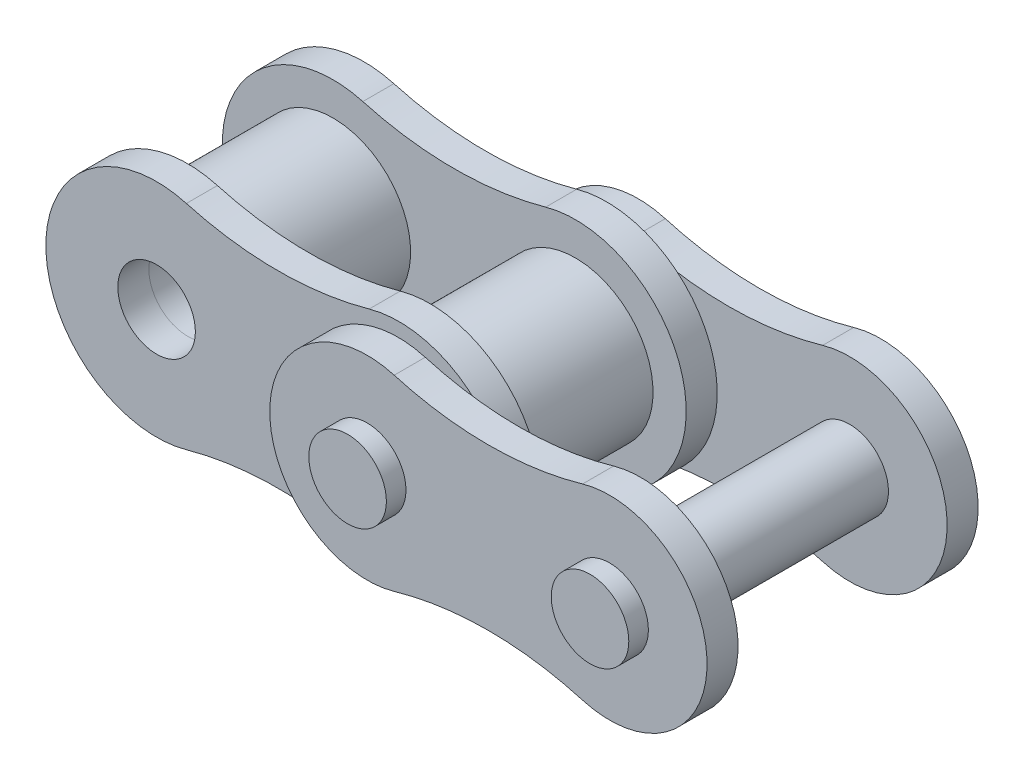
SolidWorks part; units mm, degrees
ref_plane "Front Plane" through (0, 0, 0) normal (0, 0, 1) x (1, 0, 0)
ref_plane "Top Plane" through (0, 0, 0) normal (0, 1, 0) x (1, 0, 0)
ref_plane "Right Plane" through (0, 0, 0) normal (1, 0, 0) x (0, 0, -1)
sketch "Sketch1" plane through (0, 0, 0) normal (0, 0, 1) x (1, 0, 0)
  line L0 (-7.9375, 0) -> (7.9375, 0) construction
  line L1 (-7.9375, 7.2517) -> (-7.9375, -7.2517) construction
  line L2 (0, -6.1639) -> (0, 6.1639) construction
  circle A0 centre (-7.9375, 0) radius 5.08
  circle A1 centre (7.9375, 0) radius 5.08
  circle A2 centre (-7.9375, 0) radius 2.54
  circle A3 centre (7.9375, 0) radius 2.54
  arc A4 (-5.9866, 6.9843) -> (-5.9866, -6.9843) centre (-7.9375, 0) ccw
  arc A5 (5.9866, -6.9843) -> (5.9866, 6.9843) centre (7.9375, 0) ccw
  arc A6 (-5.9866, 6.9843) -> (5.9866, 6.9843) centre (0, 28.4166) ccw
  arc A7 (-5.9866, -6.9843) -> (5.9866, -6.9843) centre (0, -28.4166) cw
  dimension "Roller Dia" = 10.16
  dimension "Pin Dia" = 5.08
  dimension "Pitch" = 15.875
  dimension "H" = 14.5034
  dimension "D2" = 12.3279
sketch "Sketch2" plane through (0, 0, 0) normal (0, 1, 0) x (1, 0, 0)
  line L0 (0, 4.7625) -> (0, -4.7625) construction
  point P2 (0, -6.7945)
  point P4 (0, 6.7945)
  point P5 (0, 6.8453)
  point P6 (0, 8.8773)
  dimension "W" = 9.525
  dimension "T" = 2.032
  dimension "D1" = 2.032
  dimension "D2" = 2.032
  dimension "D3" = 0.0508
ref_plane "Plane1" through (0, 0, 4.7625) normal (0, 0, 1) x (1, 0, 0)
ref_plane "Plane2" through (0, 0, -6.8453) normal (0, 0, 1) x (1, 0, 0)
sketch "Sketch4" plane through (0, 0, 0) normal (0, 0, 1) x (1, 0, 0)
  circle A0 centre (-7.9375, 0) radius 5.08 construction
  circle A1 centre (-7.9375, 0) radius 5.08
  circle A2 centre (7.9375, 0) radius 5.08 construction
  circle A3 centre (7.9375, 0) radius 5.08
  circle A4 centre (-7.9375, 0) radius 2.5654
  circle A5 centre (7.9375, 0) radius 2.5654
  dimension "D1" = 5.1308
  dimension "D2" = 5.1308
extrude "Boss-Extrude1" add sketch "Sketch4" along normal mid plane 9.525
sketch "Sketch5" plane through (0, 0, 4.7625) normal (0, 0, 1) x (1, 0, 0)
  arc A0 (-5.9866, 6.9843) -> (-5.9866, -6.9843) centre (-7.9375, 0) ccw construction
  arc A1 (-5.9866, 6.9843) -> (5.9866, 6.9843) centre (0, 28.4166) ccw construction
  circle A2 centre (-7.9375, 0) radius 2.54 construction
  arc A3 (5.9866, -6.9843) -> (5.9866, 6.9843) centre (7.9375, 0) ccw construction
  circle A4 centre (7.9375, 0) radius 2.54 construction
  arc A5 (5.9866, -6.9843) -> (-5.9866, -6.9843) centre (0, -28.4166) ccw construction
  arc A6 (-5.9866, 6.9843) -> (-5.9866, -6.9843) centre (-7.9375, 0) ccw
  arc A7 (-5.9866, 6.9843) -> (5.9866, 6.9843) centre (0, 28.4166) ccw
  circle A8 centre (-7.9375, 0) radius 2.54
  arc A9 (5.9866, -6.9843) -> (5.9866, 6.9843) centre (7.9375, 0) ccw
  circle A10 centre (7.9375, 0) radius 2.54
  arc A11 (5.9866, -6.9843) -> (-5.9866, -6.9843) centre (0, -28.4166) ccw
extrude "Boss-Extrude2" add sketch "Sketch5" along normal up to vertex (2.032 mm away) separate body up to point (0, 0, 6.7945)
pattern_linear "LPattern1" count 2 spacing 15.875 along (1, 0, 0) of bodies 102
sketch "Sketch7" plane through (0, 0, -6.8453) normal (0, 0, 1) x (1, 0, 0)
  line L0 (23.8125, 6.3815) -> (23.8125, -6.3815) construction
  arc A0 (9.7065, 6.1314) -> (9.7065, -6.1314) centre (7.9375, 0) ccw
  arc A1 (22.0435, -6.1314) -> (22.0435, 6.1314) centre (23.8125, 0) ccw
  arc A2 (5.9866, -6.9843) -> (5.9866, 6.9843) centre (7.9375, 0) ccw construction
  circle A3 centre (23.8125, 0) radius 5.08 construction
  arc A4 (9.7065, 6.1314) -> (22.0435, 6.1314) centre (15.875, 27.5121) ccw
  arc A5 (9.7065, -6.1314) -> (22.0435, -6.1314) centre (15.875, -27.5121) cw
  arc A6 (-5.9866, 6.9843) -> (5.9866, 6.9843) centre (0, 28.4166) ccw construction
  circle A7 centre (7.9375, 0) radius 2.54 construction
  circle A8 centre (7.9375, 0) radius 2.54
  circle A9 centre (23.8125, 0) radius 2.54
  dimension "D2" = 12.763
extrude "Boss-Extrude3" add sketch "Sketch7" against normal up to vertex (2.032 mm away) separate body up to point (0, 0, -8.8773)
mirror "Mirror1" about plane through (0, 0, 0) normal (0, 0, 1) of bodies 103 105
sketch "Sketch8" plane through (0, 0, 0) normal (0, 0, 1) x (1, 0, 0)
  circle A0 centre (7.9375, 0) radius 2.54
  circle A1 centre (23.8125, 0) radius 2.54
  circle A2 centre (7.9375, 0) radius 2.54 construction
  circle A3 centre (23.8125, 0) radius 2.54 construction
extrude "Boss-Extrude4" add sketch "Sketch8" against normal blind 10.16 and the other way blind 10.16 separate body
delete or keep bodies "Body-Delete1" type delete bodies bodies 104
equation "\"D2@Sketch1\" =\"H@Sketch1\"*.85"
equation "\"D1@Sketch2\" = \"T@Sketch2\""
equation "\"D1@Sketch4\" = \"Pin Dia@Sketch1\"+.002"
equation "\"D2@Sketch4\" = \"D1@Sketch4\""
equation "\"D1@Boss-Extrude1\" = \"W@Sketch2\""
equation "\"D2@Sketch2\" = \"T@Sketch2\""
equation "\"D3@LPattern1\" = \"Pitch@Sketch1\""
equation "\"D2@Sketch7\" = \"H@Sketch1\"*.88"
